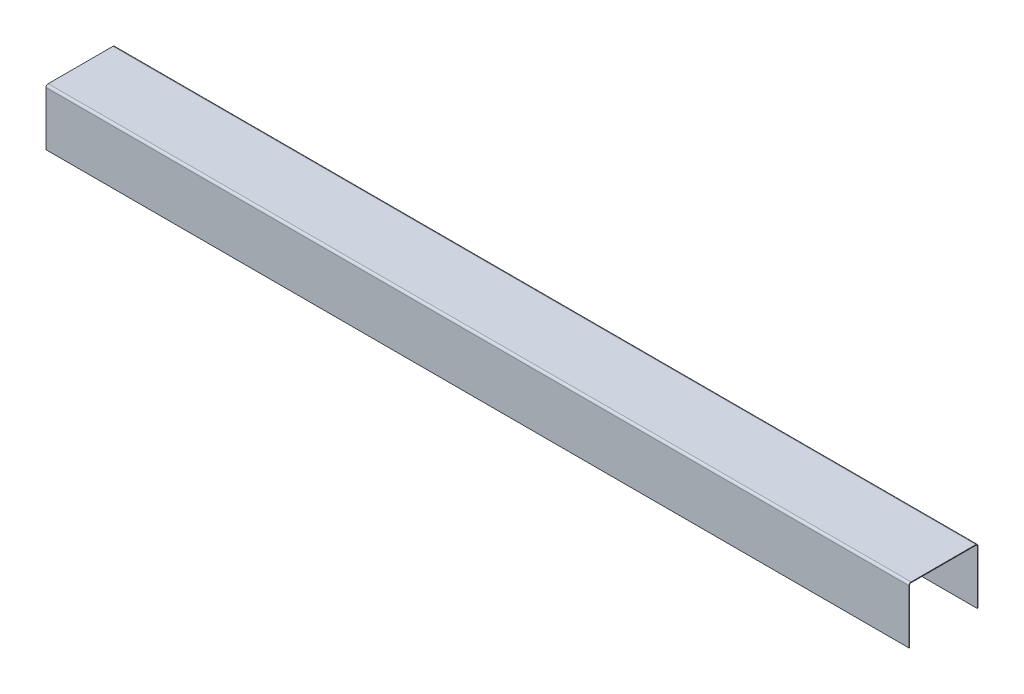
SolidWorks part; units mm, degrees
ref_plane "Front Plane" through (0, 0, 0) normal (0, 0, 1) x (1, 0, 0)
ref_plane "Top Plane" through (0, 0, 0) normal (0, 1, 0) x (1, 0, 0)
ref_plane "Right Plane" through (0, 0, 0) normal (1, 0, 0) x (0, 0, -1)
sketch "Sketch1" plane through (0, 0, 0) normal (0, 1, 0) x (1, 0, 0)
  line L0 (-10, 0) -> (990, 0) construction
  line L1 (990, 40) -> (-10, 40)
  line L2 (990, 40) -> (990, -40)
  line L3 (990, -40) -> (-10, -40)
  line L4 (-10, 40) -> (-10, -40)
  dimension "D1" = 10
  dimension "D2" = 1000
  dimension "D3" = 80
extrude "Boss-Extrude1" add sketch "Sketch1" against normal blind 65
fillet "Fillet1" radius 2.5 2 edges at (490, 0, -40) (490, 0, 40)
sketch "Sketch2" plane through (0, 0, 0) normal (1, 0, 0) x (0, 0, -1)
  line L0 (0, -40.3654) -> (0, 0) construction
  line L1 (10.3316, -55.594) -> (-10.3316, -55.594) construction
  line L2 (10.3316, -55.594) -> (10.3316, -25.1368) construction
  line L3 (10.3316, -25.1368) -> (-10.3316, -25.1368) construction
  line L4 (-10.3316, -55.594) -> (-10.3316, -25.1368) construction
  line L5 (10.3316, -55.594) -> (-10.3316, -25.1368) construction
  line L6 (10.3316, -25.1368) -> (-10.3316, -55.594) construction
  line L11 (39.2, -64.2) -> (39.2, -67.2)
  line L12 (39.2, -67.2) -> (-39.2, -67.2)
  line L13 (-39.2, -67.2) -> (-39.2, -64.2)
  line L15 (37.5, -0.8) -> (-37.5, -0.8)
  line L16 (39.2, -64.2) -> (39.2, -2.5)
  line L17 (-39.2, -64.2) -> (39.2, -64.2)
  line L18 (-39.2, -2.5) -> (-39.2, -64.2)
  line L19 (37.5, -0.8) -> (-37.5, -0.8)
  line L20 (39.2, -64.2) -> (39.2, -2.5)
  line L21 (-39.2, -64.2) -> (39.2, -64.2) construction
  line L22 (-39.2, -2.5) -> (-39.2, -64.2)
  arc A4 (39.2, -2.5) -> (37.5, -0.8) centre (37.5, -2.5) ccw
  arc A5 (-37.5, -0.8) -> (-39.2, -2.5) centre (-37.5, -2.5) ccw
  arc A6 (39.2, -2.5) -> (37.5, -0.8) centre (37.5, -2.5) ccw
  arc A7 (-37.5, -0.8) -> (-39.2, -2.5) centre (-37.5, -2.5) ccw
  point P0 (0, -40.3654)
  dimension "D1" = 0.8
  dimension "D2" = 3
extrude "Cut-Extrude1" cut sketch "Sketch2" along normal through all and the other way blind 65
equation "\"rivet_size\"=4.3"
equation "\"base_width\" = 50"
equation "\"target_width\"=80"
equation "\"D3@Sketch1\"=\"target_width\""
equation "\"bend_two_sides\"= 3.3"
equation "\"skin_panel_height\"=65"
equation "\"D1@Boss-Extrude1\"=\"skin_panel_height\""
